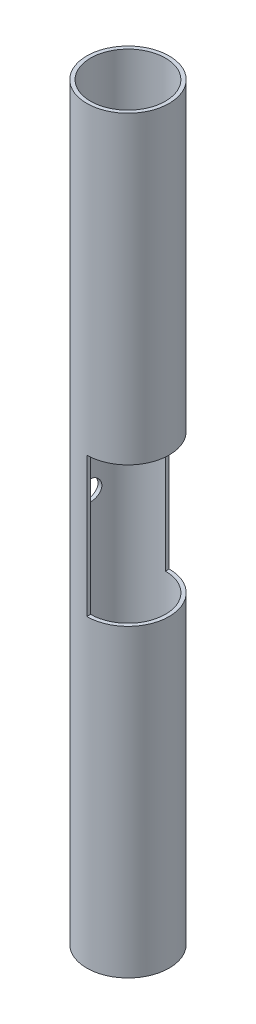
SolidWorks part; units mm, degrees
material "Thornel Mat VMA"
ref_plane "Front Plane" through (0, 0, 0) normal (0, 0, 1) x (1, 0, 0)
ref_plane "Top Plane" through (0, 0, 0) normal (0, 1, 0) x (1, 0, 0)
ref_plane "Right Plane" through (0, 0, 0) normal (1, 0, 0) x (0, 0, -1)
sketch "Sketch2" plane through (0, 0, 0) normal (0, 1, 0) x (1, 0, 0)
  circle A0 centre (0, 0) radius 15
  circle A1 centre (0, 0) radius 16.5
  dimension "D1" = 30
  dimension "D2" = 33
extrude "Boss-Extrude1" add sketch "Sketch2" along normal blind 300
sketch "Sketch3" plane through (0, 0, 0) normal (1, 0, 0) x (0, 0, -1)
  line L1 (-16.5, 300) -> (-16.5, 0) construction
  line L4 (21.2776, 178) -> (21.2776, 122)
  line L6 (-16.5, 122) -> (-16.5, 150)
  line L7 (-16.5, 150) -> (-16.5, 178)
  line L8 (21.2776, 178) -> (-14, 178)
  line L9 (-16.5, 300) -> (-16.5, 0) construction
  line L10 (-16.5, 122) -> (21.2776, 122)
  line L11 (-16.5, 178) -> (-14, 178)
extrude "Cut-Extrude1" cut sketch "Sketch3" along normal blind 28
sketch "Sketch4" plane through (0, 0, 0) normal (1, 0, 0) x (0, 0, -1)
  circle A0 centre (0, 150) radius 4
extrude "Cut-Extrude2" cut sketch "Sketch4" against normal blind 30
